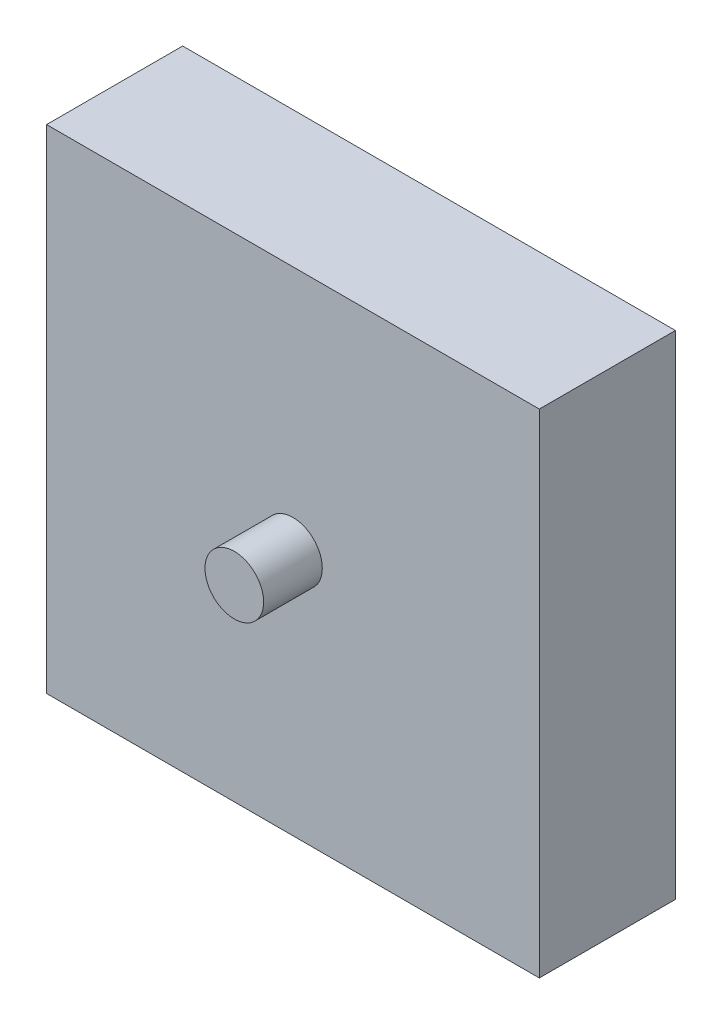
SolidWorks part; units mm, degrees
ref_plane "Front Plane" through (0, 0, 0) normal (0, 0, 1) x (1, 0, 0)
ref_plane "Top Plane" through (0, 0, 0) normal (0, 1, 0) x (1, 0, 0)
ref_plane "Right Plane" through (0, 0, 0) normal (1, 0, 0) x (0, 0, -1)
sketch "Sketch1" plane through (0, 0, 0) normal (0, 0, 1) x (1, 0, 0)
  line L1 (21, 21) -> (-21, 21)
  line L2 (21, 21) -> (21, -21)
  line L3 (21, -21) -> (-21, -21)
  line L4 (-21, 21) -> (-21, -21)
  line L5 (21, 21) -> (-21, -21) construction
  line L6 (21, -21) -> (-21, 21) construction
  point P0 (0, 0)
  dimension "D1" = 42
  dimension "D2" = 42
extrude "Boss-Extrude1" add sketch "Sketch1" along normal blind 11.6
sketch "Sketch2" plane through (0, 0, 11.6) normal (0, 0, 1) x (1, 0, 0)
  circle A0 centre (0, 0) radius 2.5
  dimension "D1" = 5
extrude "Boss-Extrude2" add sketch "Sketch2" along normal blind 5 and the other way offset from surface (18.6 mm away) 7 other way up to face at (0, 0, 0)
